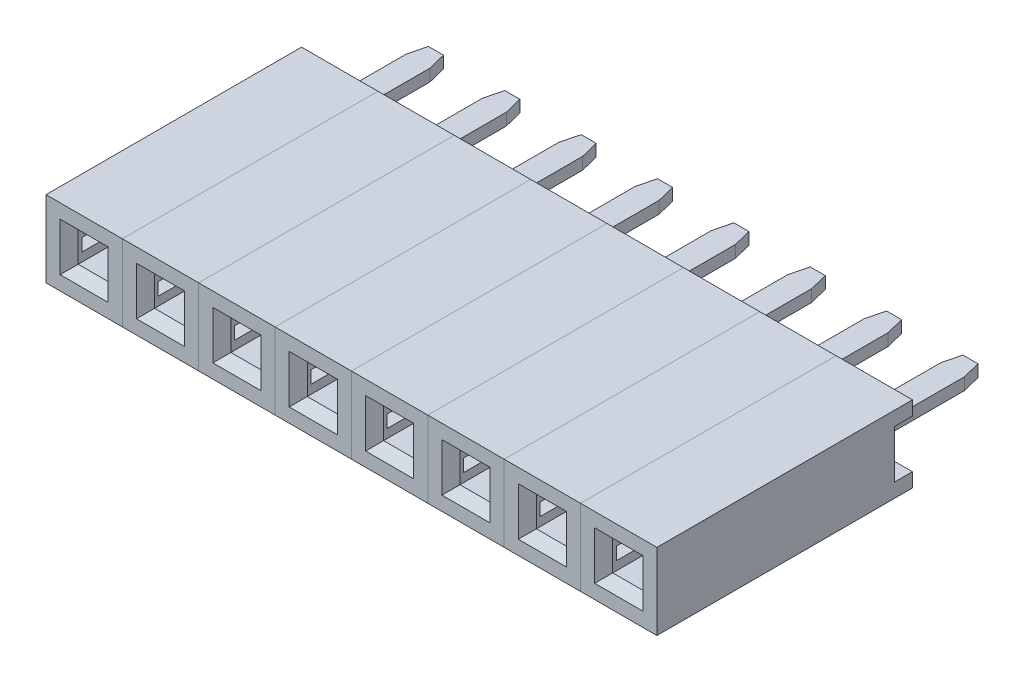
SolidWorks part; units mm, degrees
ref_plane "Спереди" through (0, 0, 0) normal (0, 0, 1) x (1, 0, 0)
ref_plane "Сверху" through (0, 0, 0) normal (0, 1, 0) x (1, 0, 0)
ref_plane "Справа" through (0, 0, 0) normal (1, 0, 0) x (0, 0, -1)
sketch "Эскиз1" plane through (0, 0, 0) normal (0, 0, 1) x (1, 0, 0)
  line L0 (0, 1.27) -> (0, 0) construction
  line L1 (1.27, 2.54) -> (-1.27, 2.54)
  line L2 (1.27, 2.54) -> (1.27, 0)
  line L3 (1.27, 0) -> (-1.27, 0)
  line L4 (-1.27, 2.54) -> (-1.27, 0)
  line L5 (1.27, 2.54) -> (-1.27, 0) construction
  line L6 (1.27, 0) -> (-1.27, 2.54) construction
  dimension "D1" = 2.54
extrude "Бобышка-Вытянуть1" add sketch "Эскиз1" along normal blind 8.5
sketch "Эскиз2" plane through (0, 0, 0) normal (0, 0, -1) x (-1, 0, 0)
  line L0 (0, 1.27) -> (0, 0) construction
  line L1 (1, 1.48) -> (-1, 1.48)
  line L2 (1, 1.48) -> (1, 1.06)
  line L3 (1, 1.06) -> (-1, 1.06)
  line L4 (-1, 1.48) -> (-1, 1.06)
  line L5 (1, 1.48) -> (-1, 1.06) construction
  line L6 (1, 1.06) -> (-1, 1.48) construction
  line L7 (0, 1.27) -> (-1.27, 1.27) construction
  line L8 (-1.27, 0) -> (-1.27, 2.54) construction
  point P0 (0, 1.27)
  dimension "D1" = 2
  dimension "D2" = 0.42
extrude "Вырез-Вытянуть1" cut sketch "Эскиз2" against normal offset from surface (8.08 mm away) 0.42 up to face at (0, 1.27, 8.5)
sketch "Эскиз3" plane through (0, 0, 8.5) normal (0, 0, 1) x (1, 0, 0)
  line L0 (0, 1.27) -> (-1.27, 1.27) construction
  line L1 (-0.5, 0.77) -> (0.5, 0.77)
  line L2 (-0.5, 0.77) -> (-0.5, 1.77)
  line L3 (-0.5, 1.77) -> (0.5, 1.77)
  line L4 (0.5, 0.77) -> (0.5, 1.77)
  line L5 (-0.5, 0.77) -> (0.5, 1.77) construction
  line L6 (-0.5, 1.77) -> (0.5, 0.77) construction
  line L7 (-1.27, 2.54) -> (-1.27, 0) construction
  line L8 (0, 1.27) -> (0, 0) construction
  line L9 (-1.27, 0) -> (1.27, 0) construction
  point P0 (0, 1.27)
  dimension "D1" = 1
  dimension "D2" = 1
extrude "Вырез-Вытянуть2" cut sketch "Эскиз3" against normal offset from surface (6.5 mm away) 2 up to face at (0, 1.27, 0)
sketch "Эскиз4" plane through (-1.27, 0, 0) normal (-1, 0, 0) x (0, 0, 1)
  line L0 (0, 2.54) -> (0, 0) construction
  line L1 (0.6, 0.47) -> (0, 0.47)
  line L2 (0.6, 0.47) -> (0.6, 2.07)
  line L3 (0.6, 2.07) -> (0, 2.07)
  line L4 (0, 0.47) -> (0, 2.07)
  line L5 (0.6, 0.47) -> (0, 2.07) construction
  line L6 (0.6, 2.07) -> (0, 0.47) construction
  line L7 (0.3, 1.27) -> (0, 1.27) construction
  point P0 (0.3, 1.27)
  dimension "D1" = 0.6
  dimension "D2" = 1.6
extrude "Вырез-Вытянуть3" cut sketch "Эскиз4" against normal through all
ref_plane "Плоскость1" through (0, 1.27, 0) normal (0, -1, 0) x (-1, 0, 0)
sketch "Эскиз6" plane through (0, 1.27, 0) normal (0, -1, 0) x (-1, 0, 0)
  line L1 (-1, -8.08) -> (-1, -0.6) construction
  line L2 (1, -8.08) -> (1, -0.6) construction
  line L4 (-1.27, 0) -> (1.27, 0) construction
  line L10 (-1, -0.6) -> (1, -0.6) construction
  line L18 (-0.4, 0) -> (0.4, 0)
  line L19 (-0.6, -0.6) -> (-0.4, -0.6)
  line L20 (-1, -2.6) -> (-1, -0.85)
  line L21 (1, -2.6) -> (1, -0.85)
  line L22 (-0.4, -0.6) -> (-0.4, 0)
  line L23 (0.4, -0.6) -> (0.4, 0)
  line L24 (0, 0) -> (0, -0.6) construction
  line L25 (-1, -2.6) -> (-0.8133, -6.1)
  line L26 (-0.8133, -6.1) -> (-0.45, -6.75)
  line L27 (-0.45, -6.75) -> (-0.3, -6.35)
  line L28 (-0.3, -6.35) -> (-0.5, -2.6)
  line L29 (-0.5, -2.6) -> (-0.5, -1.7)
  line L30 (-0.5, -1.7) -> (0, -1.7) construction
  line L31 (0.5, -1.7) -> (0.5, -2.6)
  line L32 (0.5, -2.6) -> (0.3, -6.35)
  line L33 (0.3, -6.35) -> (0.45, -6.75)
  line L34 (0.45, -6.75) -> (0.8133, -6.1)
  line L35 (0.8133, -6.1) -> (1, -2.6)
  line L36 (-1, -2.6) -> (-0.5, -2.6) construction
  line L37 (0.5, -2.6) -> (-0.5, -2.6) construction
  line L38 (1, -2.6) -> (0.5, -2.6) construction
  line L39 (-0.3, -6.35) -> (0.3, -6.35) construction
  line L40 (-0.45, -6.75) -> (0.45, -6.75) construction
  line L41 (-0.8133, -6.1) -> (0.8133, -6.1) construction
  line L42 (0, -1.7) -> (0.5, -1.7) construction
  line L43 (0, -1.7) -> (0, -0.6) construction
  line L44 (-1, -0.85) -> (-0.6, -0.6)
  line L45 (1, -0.85) -> (0.6, -0.6)
  line L46 (-1, -0.85) -> (1, -0.85) construction
  line L47 (0.4, -0.6) -> (0.6, -0.6)
  arc A0 (-0.5, -1.7) -> (0.5, -1.7) centre (0, -1.7) cw
  dimension "D1" = 0.8
  dimension "D2" = 0.6
  dimension "D3" = 1
  dimension "D4" = 1.2
  dimension "D5" = 0.25
  dimension "D6" = 1.1
  dimension "D7" = 2
  dimension "D8" = 0.4
  dimension "D9" = 0.25
  dimension "D10" = 3.5
  dimension "D11" = 0.9
  dimension "D12" = 1.2
extrude "Бобышка-Вытянуть2" add sketch "Эскиз6" along normal mid plane 0.4 separate body contours L29 A0 L31 L32 L33 L34 L35 L21 L45 L19 L44 L20 L25 L26 L27 L28 | L19 L23 L18 L22
chamfer "Фаска1" distance 0.3 angle 45 4 edges at (0, 0.77, 8.5) (0.5, 1.27, 8.5) (0, 1.77, 8.5) (-0.5, 1.27, 8.5)
sketch "Sketch1" plane through (0, 0, 0) normal (0, 0, -1) x (-1, 0, 0)
  line L1 (-0.4, 1.47) -> (0.4, 1.47)
  line L2 (-0.4, 1.47) -> (-0.4, 1.07)
  line L3 (-0.4, 1.07) -> (0.4, 1.07)
  line L4 (0.4, 1.47) -> (0.4, 1.07)
extrude "Boss-Extrude1" add sketch "Sketch1" along normal blind 3.2
sketch "Sketch2" plane through (0, 1.47, 0) normal (0, 1, 0) x (1, 0, 0)
  line L0 (-0.4, 2.6) -> (0.4, 2.6) construction
  line L1 (-0.4, -0.6) -> (-0.4, 3.2) construction
  line L2 (0.4, -0.6) -> (0.4, 3.2) construction
  line L3 (-0.4, 3.2) -> (0.4, 3.2) construction
  line L4 (0, 3.2) -> (0, 2.6) construction
  line L5 (-0.25, 3.2) -> (-0.25, 2.6) construction
  line L6 (-0.25, 3.2) -> (-0.4, 2.6)
  line L7 (-0.4, 2.6) -> (-0.5333, 2.6)
  line L8 (-0.5333, 2.6) -> (-0.5333, 3.3233)
  line L9 (-0.5333, 3.3233) -> (-0.25, 3.3233)
  line L10 (-0.25, 3.3233) -> (-0.25, 3.2)
  line L11 (-0.25, 3.2) -> (-0.2501, 3.2095)
  line L12 (0.4, 2.6) -> (0.5333, 2.6)
  line L13 (0.25, 3.2) -> (0.4, 2.6)
  line L14 (0.25, 3.3233) -> (0.25, 3.2)
  line L15 (0.5333, 2.6) -> (0.5333, 3.3233)
  line L16 (0.5333, 3.3233) -> (0.25, 3.3233)
  dimension "D1" = 0.6
  dimension "D2" = 0.25
extrude "Cut-Extrude1" cut sketch "Sketch2" against normal blind 1
pattern_linear "LPattern1" count 8 spacing 2.54 along (1, 0, 0) of bodies 127
